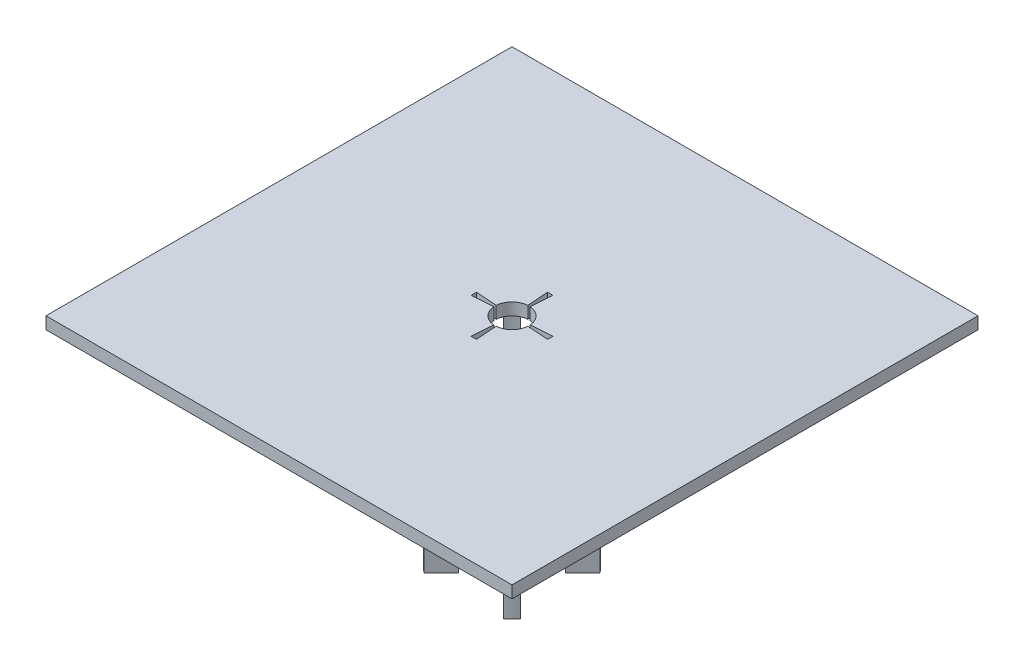
SolidWorks part; units mm, degrees
ref_plane "Front Plane" through (0, 0, 0) normal (0, 0, 1) x (1, 0, 0)
ref_plane "Top Plane" through (0, 0, 0) normal (0, 1, 0) x (1, 0, 0)
ref_plane "Right Plane" through (0, 0, 0) normal (1, 0, 0) x (0, 0, -1)
sketch "Sketch2" plane through (0, 0, 0) normal (0, 1, 0) x (1, 0, 0)
  line L0 (0, 3.15) -> (0, -3.15) construction
  line L1 (-19.185, 19.185) -> (19.185, 19.185)
  line L2 (-19.185, 19.185) -> (-19.185, -19.185)
  line L3 (-19.185, -19.185) -> (19.185, -19.185)
  line L4 (19.185, 19.185) -> (19.185, -19.185)
  line L5 (-19.185, 19.185) -> (19.185, -19.185) construction
  line L6 (-19.185, -19.185) -> (19.185, 19.185) construction
  line L7 (-3.15, 0) -> (3.15, 0) construction
  line L31 (-1.8439, 2.551) -> (-3.2698, 3.9769)
  line L32 (-2.551, 1.8439) -> (-3.9769, 3.2698)
  line L33 (-0.0977, 1.3966) -> (-0.2196, 3.1399)
  line L34 (0.0977, 1.3966) -> (0.2196, 3.1399)
  line L35 (1.3966, -0.0977) -> (3.1399, -0.2196)
  line L36 (1.3966, 0.0977) -> (3.1399, 0.2196)
  line L37 (2.551, 1.8439) -> (3.9769, 3.2698)
  line L38 (1.8439, 2.551) -> (3.2698, 3.9769)
  line L39 (-0.0977, -1.3966) -> (-0.2196, -3.1399)
  line L40 (0.0977, -1.3966) -> (0.2196, -3.1399)
  line L41 (1.8439, -2.551) -> (3.2698, -3.9769)
  line L42 (2.551, -1.8439) -> (3.9769, -3.2698)
  line L43 (-1.3966, 0.0977) -> (-3.1399, 0.2196)
  line L44 (-1.3966, -0.0977) -> (-3.1399, -0.2196)
  line L45 (-2.551, -1.8439) -> (-3.9769, -3.2698)
  line L46 (-1.8439, -2.551) -> (-3.2698, -3.9769)
  circle A2 centre (0, 0) radius 5.1485 construction
  circle A25 centre (0, 0) radius 3.1476 construction
  circle A26 centre (0, 0) radius 1.4 construction
  circle A27 centre (0, 0) radius 1.4
  arc A33 (-3.9769, 3.2698) -> (-3.2698, 3.9769) centre (0, 0) cw
  arc A34 (-2.551, 1.8439) -> (-1.8439, 2.551) centre (0, 0) cw
  arc A35 (-0.2196, 3.1399) -> (0.2196, 3.1399) centre (0, 0) cw
  arc A36 (-0.0977, 1.3966) -> (0.0977, 1.3966) centre (0, 0) cw
  arc A37 (1.3966, 0.0977) -> (1.3966, -0.0977) centre (0, 0) cw
  arc A38 (3.1399, 0.2196) -> (3.1399, -0.2196) centre (0, 0) cw
  arc A39 (1.8439, 2.551) -> (2.551, 1.8439) centre (0, 0) cw
  arc A40 (3.2698, 3.9769) -> (3.9769, 3.2698) centre (0, 0) cw
  arc A41 (0.0977, -1.3966) -> (-0.0977, -1.3966) centre (0, 0) cw
  arc A42 (0.2196, -3.1399) -> (-0.2196, -3.1399) centre (0, 0) cw
  arc A43 (2.551, -1.8439) -> (1.8439, -2.551) centre (0, 0) cw
  arc A44 (3.9769, -3.2698) -> (3.2698, -3.9769) centre (0, 0) cw
  arc A45 (-1.3966, -0.0977) -> (-1.3966, 0.0977) centre (0, 0) cw
  arc A46 (-3.1399, -0.2196) -> (-3.1399, 0.2196) centre (0, 0) cw
  arc A47 (-1.8439, -2.551) -> (-2.551, -1.8439) centre (0, 0) cw
  arc A48 (-3.2698, -3.9769) -> (-3.9769, -3.2698) centre (0, 0) cw
  point P0 (0, 0)
  point P28 (0, 0)
  point P50 (0, 0)
  point P55 (0, 0)
  point P100 (0, 0)
  dimension "D6" = 4
  dimension "D7" = 4
  dimension "D2" = 0.5
  dimension "D3" = 38.37
  dimension "D4" = 38.37
  dimension "D8" = 4
  dimension "D5" = 0.5
sketch "Sketch7" plane through (0, 0, 0) normal (0, 1, 0) x (1, 0, 0)
  line L1 (-19.185, 19.185) -> (19.185, 19.185)
  line L2 (-19.185, 19.185) -> (-19.185, -19.185)
  line L3 (-19.185, -19.185) -> (19.185, -19.185)
  line L4 (19.185, 19.185) -> (19.185, -19.185)
  line L5 (-19.185, 19.185) -> (19.185, -19.185) construction
  line L6 (-19.185, -19.185) -> (19.185, 19.185) construction
  line L8 (-2.551, 1.8439) -> (-3.9769, 3.2698)
  line L9 (-3.2698, 3.9769) -> (-1.8439, 2.551)
  line L10 (3.9769, 3.2698) -> (2.551, 1.8439)
  line L11 (1.8439, 2.551) -> (3.2698, 3.9769)
  line L14 (3.2698, -3.9769) -> (1.8439, -2.551)
  line L15 (2.551, -1.8439) -> (3.9769, -3.2698)
  line L18 (-3.9769, -3.2698) -> (-2.551, -1.8439)
  line L19 (-1.8439, -2.551) -> (-3.2698, -3.9769)
  arc A2 (-3.9769, 3.2698) -> (-3.2698, 3.9769) centre (0, 0) cw
  arc A5 (3.2698, 3.9769) -> (3.9769, 3.2698) centre (0, 0) cw
  arc A9 (3.9769, -3.2698) -> (3.2698, -3.9769) centre (0, 0) cw
  arc A13 (-3.2698, -3.9769) -> (-3.9769, -3.2698) centre (0, 0) cw
  circle A33 centre (0, 0) radius 3.1476
  point P0 (0, 0)
  point P54 (0, 0)
  dimension "D2" = 6.2952
  dimension "D1" = 4
extrude "Boss-Extrude6" add sketch "Sketch2" along normal blind 1 contours L4 L1 L2 L3 A34 L32 A33 L31 L38 A40 L37 A39 L42 A44 L41 A43 L44 A46 L43 A27 L33 A35 L34 L36 A38 L35 L40 A42 L39 L46 A48 L45 A47 | A48 L46 A47 L45 | L32 A34 L31 A33 | A40 L38 A39 L37 | A44 L42 A43 L41
sketch "Sketch8" plane through (0, 1, 0) normal (0, 1, 0) x (1, 0, 0)
  line L0 (-1.3966, 0.0977) -> (-3.1399, 0.2196)
  line L1 (-0.0977, 1.3966) -> (-0.2196, 3.1399)
  line L2 (-2.551, 1.8439) -> (-3.9769, 3.2698)
  line L3 (-3.2698, 3.9769) -> (-1.8439, 2.551)
  line L4 (1.3966, 0.0977) -> (3.1399, 0.2196)
  line L5 (0.0977, 1.3966) -> (0.2196, 3.1399)
  line L6 (3.9769, 3.2698) -> (2.551, 1.8439)
  line L7 (1.8439, 2.551) -> (3.2698, 3.9769)
  line L8 (0.0977, -1.3966) -> (0.2196, -3.1399)
  line L9 (1.3966, -0.0977) -> (3.1399, -0.2196)
  line L10 (3.2698, -3.9769) -> (1.8439, -2.551)
  line L11 (2.551, -1.8439) -> (3.9769, -3.2698)
  line L12 (-1.3966, -0.0977) -> (-3.1399, -0.2196)
  line L13 (-0.0977, -1.3966) -> (-0.2196, -3.1399)
  line L14 (-3.9769, -3.2698) -> (-2.551, -1.8439)
  line L15 (-1.8439, -2.551) -> (-3.2698, -3.9769)
  arc A0 (-3.1399, 0.2196) -> (-0.2196, 3.1399) centre (0, 0) cw
  arc A1 (-1.3966, 0.0977) -> (-0.0977, 1.3966) centre (0, 0) cw
  arc A2 (-3.9769, 3.2698) -> (-3.2698, 3.9769) centre (0, 0) cw
  arc A3 (-2.551, 1.8439) -> (-1.8439, 2.551) centre (0, 0) cw
  arc A4 (0.0977, 1.3966) -> (1.3966, 0.0977) centre (0, 0) cw
  arc A5 (0.2196, 3.1399) -> (3.1399, 0.2196) centre (0, 0) cw
  arc A6 (1.8439, 2.551) -> (2.551, 1.8439) centre (0, 0) cw
  arc A7 (3.2698, 3.9769) -> (3.9769, 3.2698) centre (0, 0) cw
  arc A8 (1.3966, -0.0977) -> (0.0977, -1.3966) centre (0, 0) cw
  arc A9 (3.1399, -0.2196) -> (0.2196, -3.1399) centre (0, 0) cw
  arc A10 (2.551, -1.8439) -> (1.8439, -2.551) centre (0, 0) cw
  arc A11 (3.9769, -3.2698) -> (3.2698, -3.9769) centre (0, 0) cw
  arc A12 (-0.0977, -1.3966) -> (-1.3966, -0.0977) centre (0, 0) cw
  arc A13 (-0.2196, -3.1399) -> (-3.1399, -0.2196) centre (0, 0) cw
  arc A14 (-1.8439, -2.551) -> (-2.551, -1.8439) centre (0, 0) cw
  arc A15 (-3.2698, -3.9769) -> (-3.9769, -3.2698) centre (0, 0) cw
  point P47 (0, 0)
  dimension "D1" = 4
extrude "Boss-Extrude7" add sketch "Sketch7" against normal blind 17
